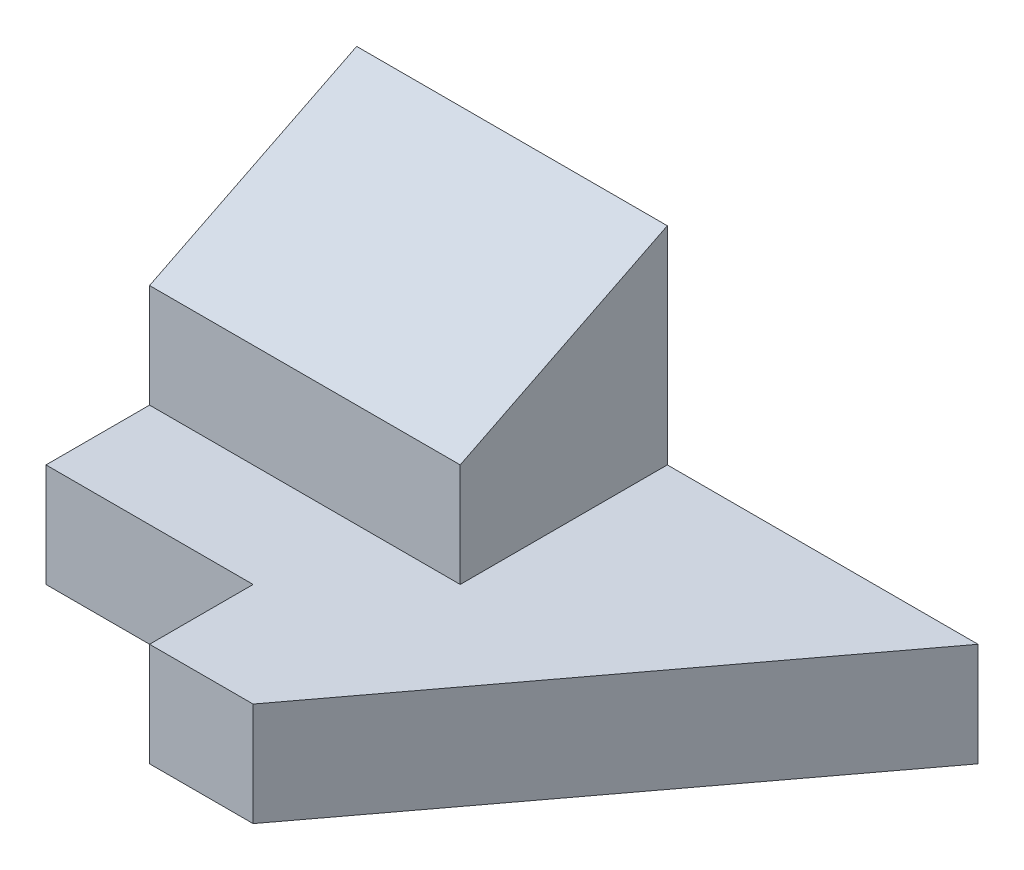
SolidWorks part; units mm, degrees
ref_plane "Front Plane" through (0, 0, 0) normal (0, 0, 1) x (1, 0, 0)
ref_plane "Top Plane" through (0, 0, 0) normal (0, 1, 0) x (1, 0, 0)
ref_plane "Right Plane" through (0, 0, 0) normal (1, 0, 0) x (0, 0, -1)
sketch "Sketch1" plane through (0, 0, 0) normal (0, 1, 0) x (1, 0, 0)
  line L0 (-38.8312, 33.6364) -> (-38.8312, 3.6364)
  line L1 (-38.8312, 3.6364) -> (-18.8312, 3.6364)
  line L2 (-18.8312, 3.6364) -> (-18.8312, -6.3636)
  line L3 (-18.8312, -6.3636) -> (-8.8312, -6.3636)
  line L4 (-8.8312, -6.3636) -> (21.1688, 33.6364)
  line L5 (21.1688, 33.6364) -> (-38.8312, 33.6364)
  dimension "D1" = 30
  dimension "D2" = 20
  dimension "D3" = 10
  dimension "D4" = 60
  dimension "D5" = 10
extrude "Boss-Extrude1" add sketch "Sketch1" along normal blind 10
sketch "Sketch2" plane through (-38.8312, 0, 0) normal (-1, 0, 0) x (0, 0, 1)
  line L0 (-33.6364, 10) -> (-33.6364, 30)
  line L1 (-33.6364, 30) -> (-13.6364, 20)
  line L2 (-13.6364, 20) -> (-13.6364, 10)
  line L3 (-33.6364, 10) -> (-3.6364, 10) construction
  line L4 (-13.6364, 10) -> (-33.6364, 10)
  dimension "D1" = 20
  dimension "D2" = 20
  dimension "D3" = 10
extrude "Boss-Extrude2" add sketch "Sketch2" against normal blind 30 contours L1 L2 L4 L0
